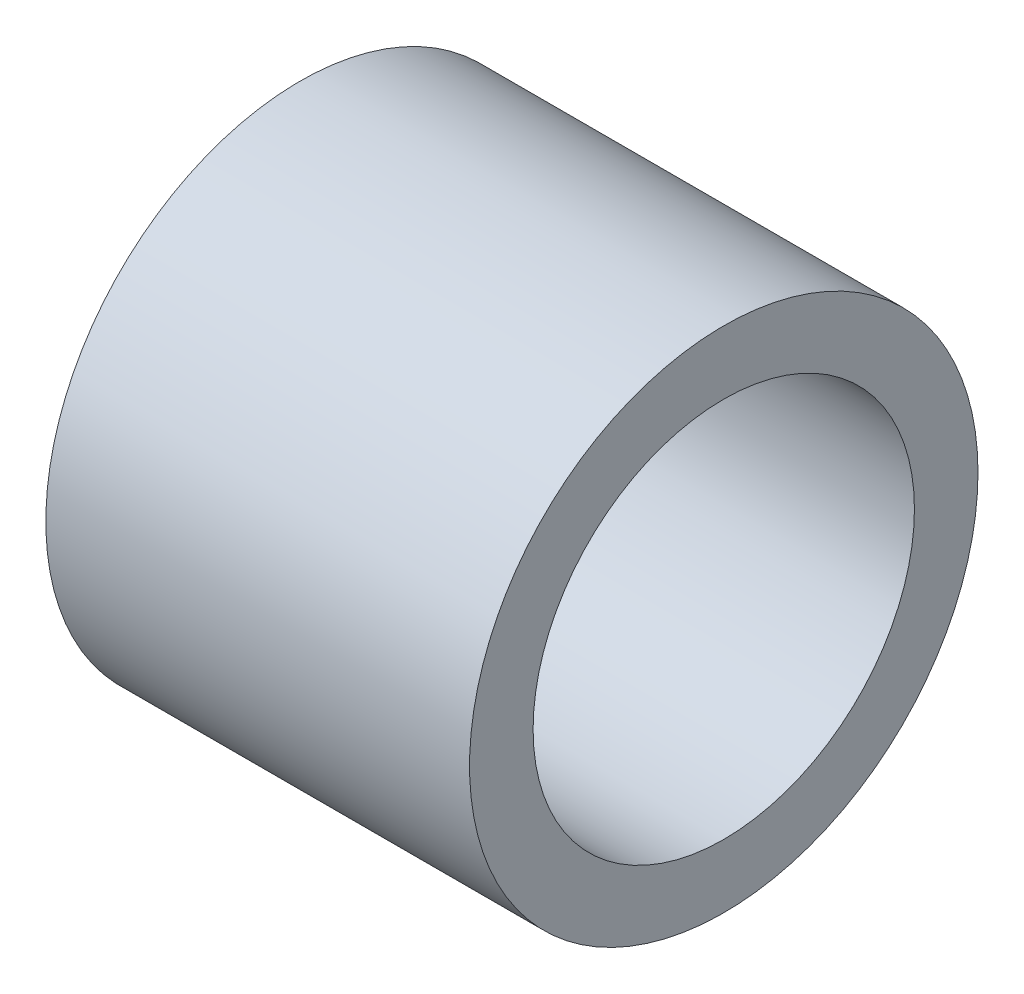
SolidWorks part; units mm, degrees
ref_plane "Front Plane" through (0, 0, 0) normal (0, 0, 1) x (1, 0, 0)
ref_plane "Top Plane" through (0, 0, 0) normal (0, 1, 0) x (1, 0, 0)
ref_plane "Right Plane" through (0, 0, 0) normal (1, 0, 0) x (0, 0, -1)
sketch "Sketch1" plane through (0, 0, 0) normal (1, 0, 0) x (0, 0, -1)
  line L0 (-0.024, 0.0361) -> (-0.012, 2.25) construction
  line L1 (-0.003, 3.9014) -> (-0.0086, 3) construction
  line L2 (-0.0133, 2.25) -> (-0.0414, -2.2496) construction
  line L3 (-0.0079, 3) -> (-0.003, 3.9014) construction
  line L4 (-0.0461, -2.9986) -> (-0.0483, -3.3439) construction
  circle A0 centre (0, 0) radius 2.25
  circle A1 centre (0, 0) radius 3
  arc A2 (-0.7395, 2.125) -> (0.7395, 2.125) centre (0, 2.25) ccw
  arc A3 (-0.0461, -2.9986) -> (0, -3) centre (0, -2.25) ccw
  arc A4 (0, 3) -> (-0.0086, 3) centre (0, 2.25) ccw
  arc A5 (0.7395, -2.125) -> (-0.7395, -2.125) centre (0, -2.25) ccw
  point P11 (-5.7596, -2.8738)
extrude "Boss-Extrude1" add sketch "Sketch1" along normal mid plane 5 contours A0 | A1
